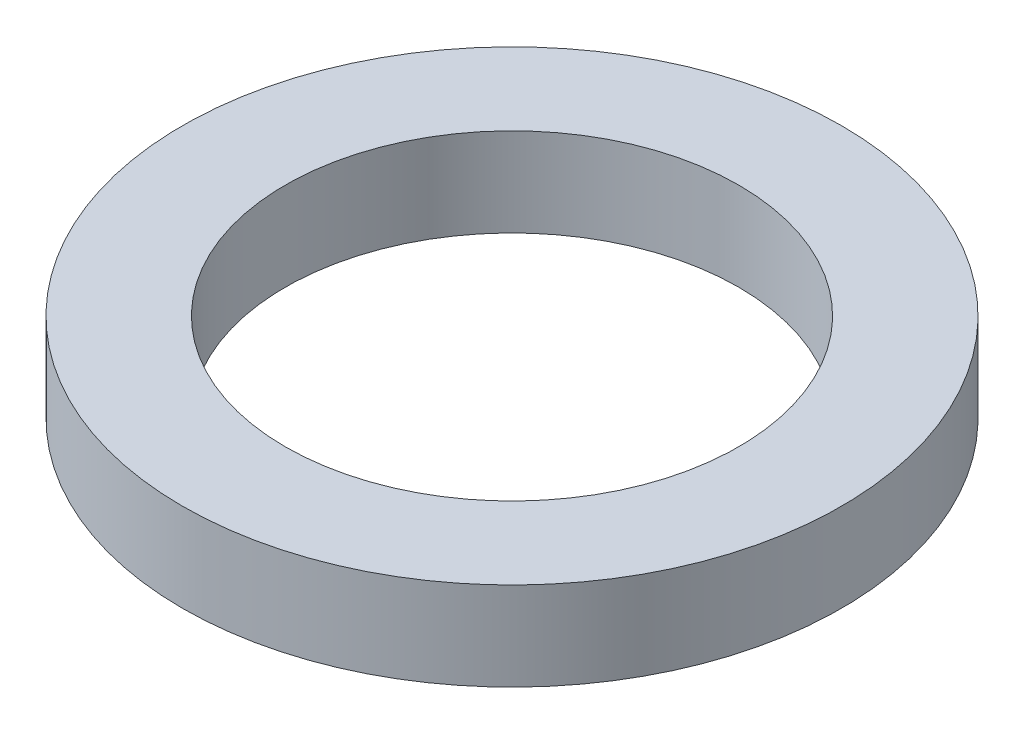
SolidWorks part; units mm, degrees
ref_plane "Front Plane" through (0, 0, 0) normal (0, 0, 1) x (1, 0, 0)
ref_plane "Top Plane" through (0, 0, 0) normal (0, 1, 0) x (1, 0, 0)
ref_plane "Right Plane" through (0, 0, 0) normal (1, 0, 0) x (0, 0, -1)
sketch "Sketch1" plane through (0, 0, 0) normal (0, 1, 0) x (1, 0, 0)
  circle A0 centre (0, 0) radius 7.45
  circle A1 centre (0, 0) radius 5.125
  dimension "D1" = 14.9
  dimension "D2" = 10.25
extrude "Boss-Extrude1" add sketch "Sketch1" along normal blind 2
